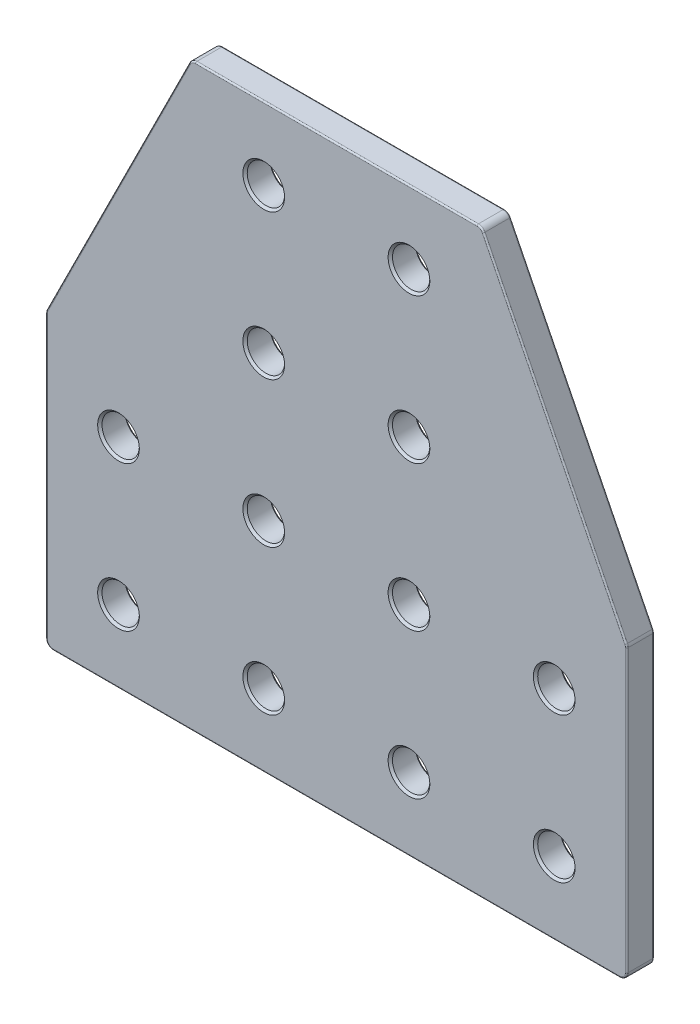
SolidWorks part; units mm, degrees
ref_plane "Front Plane" through (0, 0, 0) normal (0, 0, 1) x (1, 0, 0)
ref_plane "Top Plane" through (0, 0, 0) normal (0, 1, 0) x (1, 0, 0)
ref_plane "Right Plane" through (0, 0, 0) normal (1, 0, 0) x (0, 0, -1)
sketch "Sketch1" plane through (0, 0, 0) normal (0, 0, 1) x (1, 0, 0)
  line L0 (0, 50.8) -> (0, -50.8) construction
  line L1 (-50.8, -50.8) -> (50.8, -50.8) construction
  line L2 (-25.4, 50.8) -> (25.4, 50.8) construction
  line L3 (-25.4, 50.8) -> (-50.8, 0) construction
  line L4 (-50.8, 0) -> (-50.8, -50.8) construction
  line L5 (25.4, 50.8) -> (50.8, 0) construction
  line L6 (50.8, 0) -> (50.8, -50.8) construction
  line L7 (-38.1, -38.1) -> (-12.7, -38.1) construction
  line L8 (-41.275, -38.1) -> (-40.005, -38.1) construction
  line L9 (-38.1, -38.1) -> (-38.1, -12.7) construction
  circle A0 centre (-38.1, -38.1) radius 3.2639
  circle A1 centre (-38.1, -38.1) radius 3.175 construction
  dimension "D2" = 6.5278
  dimension "Mounting Fastener Thread Size" = 6.35
  dimension "D1" = 101.6
  dimension "Length" = 101.6
  dimension "Side Flat" = 50.8
  dimension "Top Flat" = 50.8
  dimension "D3" = 25.4
  dimension "D4" = 12.7
  dimension "D5" = 12.7
  dimension "Mounting Fastener Thread Pitch" = 1.27
sketch "Sketch2" plane through (0, 0, 0) normal (1, 0, 0) x (0, 0, -1)
  line L0 (-2.3876, -38.1) -> (2.3876, -38.1) construction
  line L1 (2.3876, -38.1) -> (10.3124, -38.1) construction
  point P2 (0, -38.1)
  dimension "Thickness" = 4.7752
  dimension "Mounting Fastener Thread Length" = 12.7
sketch "Sketch3" plane through (0, 0, 0) normal (0, 0, 1) x (1, 0, 0)
  line L0 (25.4, 50.8) -> (50.8, 0) construction
  line L1 (-25.4, 50.8) -> (25.4, 50.8) construction
  line L2 (-25.4, 50.8) -> (-50.8, 0) construction
  line L3 (-50.8, 0) -> (-50.8, -50.8) construction
  line L4 (-50.8, -50.8) -> (50.8, -50.8) construction
  line L5 (50.8, 0) -> (50.8, -50.8) construction
  line L6 (25.4, 50.8) -> (50.8, 0)
  line L7 (-25.4, 50.8) -> (25.4, 50.8)
  line L8 (-25.4, 50.8) -> (-50.8, 0)
  line L9 (-50.8, 0) -> (-50.8, -50.8)
  line L10 (-50.8, -50.8) -> (50.8, -50.8)
  line L11 (50.8, 0) -> (50.8, -50.8)
  circle A0 centre (-38.1, -38.1) radius 3.2639 construction
  circle A1 centre (-38.1, -38.1) radius 3.2639
  circle A2 centre (-12.7, -38.1) radius 3.2639
  circle A3 centre (12.7, -38.1) radius 3.2639
  circle A4 centre (38.1, -38.1) radius 3.2639
  circle A5 centre (-12.7, -12.7) radius 3.2639
  circle A6 centre (12.7, -12.7) radius 3.2639
  circle A7 centre (38.1, -12.7) radius 3.2639
  circle A8 centre (-12.7, 12.7) radius 3.2639
  circle A9 centre (12.7, 12.7) radius 3.2639
  circle A10 centre (38.1, 12.7) radius 3.2639 construction
  circle A11 centre (-12.7, 38.1) radius 3.2639
  circle A12 centre (12.7, 38.1) radius 3.2639
  circle A13 centre (38.1, 38.1) radius 3.2639 construction
  circle A14 centre (-38.1, -12.7) radius 3.2639
  circle A15 centre (-38.1, 12.7) radius 3.2639 construction
  circle A16 centre (-38.1, 38.1) radius 3.2639 construction
  dimension "D2" = 4
  dimension "D1" = 4
extrude "Boss-Extrude1" add sketch "Sketch3" against normal up to vertex (2.3876 mm away) from vertex at 2.3876 starting at point (0, -38.1, 2.3876)
fillet "Fillet1" radius 1.27 6 edges at (-25.4, 50.8, 0) (-50.8, 0, 0) (-50.8, -50.8, 0) (25.4, 50.8, 0) (50.8, -50.8, 0) (50.8, 0, 0)
chamfer "Chamfer1" distance 0.381 angle 45 24 edges at (-9.4361, 12.7, 2.3876) (-9.4361, 12.7, -2.3876) (15.9639, 12.7, 2.3876) (15.9639, 12.7, -2.3876) (15.9639, -12.7, 2.3876) (15.9639, -12.7, -2.3876) (41.3639, -12.7, 2.3876) (41.3639, -12.7, -2.3876) (41.3639, -38.1, 2.3876) (41.3639, -38.1, -2.3876) (15.9639, -38.1, 2.3876) (15.9639, -38.1, -2.3876) (-9.4361, -38.1, 2.3876) (-9.4361, -38.1, -2.3876) (-9.4361, -12.7, 2.3876) (-9.4361, -12.7, -2.3876) (-34.8361, -12.7, 2.3876) (-34.8361, -12.7, -2.3876) (-34.8361, -38.1, 2.3876) (-34.8361, -38.1, -2.3876) (15.9639, 38.1, 2.3876) (15.9639, 38.1, -2.3876) (-9.4361, 38.1, 2.3876) (-9.4361, 38.1, -2.3876)
fillet "Fillet2" radius 0.254 24 edges at (50.766, -0.008, 2.3876) (50.8, -24.9149, 2.3876) (50.428, -50.428, 2.3876) (0, -50.8, 2.3876) (-50.428, -50.428, 2.3876) (-50.8, -24.9149, 2.3876) (-50.766, -0.008, 2.3876) (-38.2085, 25.1831, 2.3876) (-25.2828, 50.6103, 2.3876) (0, 50.8, 2.3876) (25.2828, 50.6103, 2.3876) (50.766, -0.008, -2.3876) (50.8, -24.9149, -2.3876) (50.428, -50.428, -2.3876) (0, -50.8, -2.3876) (-50.428, -50.428, -2.3876) (-50.8, -24.9149, -2.3876) (-50.766, -0.008, -2.3876) (-38.2085, 25.1831, -2.3876) (-25.2828, 50.6103, -2.3876) (0, 50.8, -2.3876) (25.2828, 50.6103, -2.3876) (38.2085, 25.1831, 2.3876) (38.2085, 25.1831, -2.3876)
equation "\"D5@Sketch1\"=\"D4@Sketch1\""
equation "\"D1@Sketch1\"=\"Length@Sketch1\""
